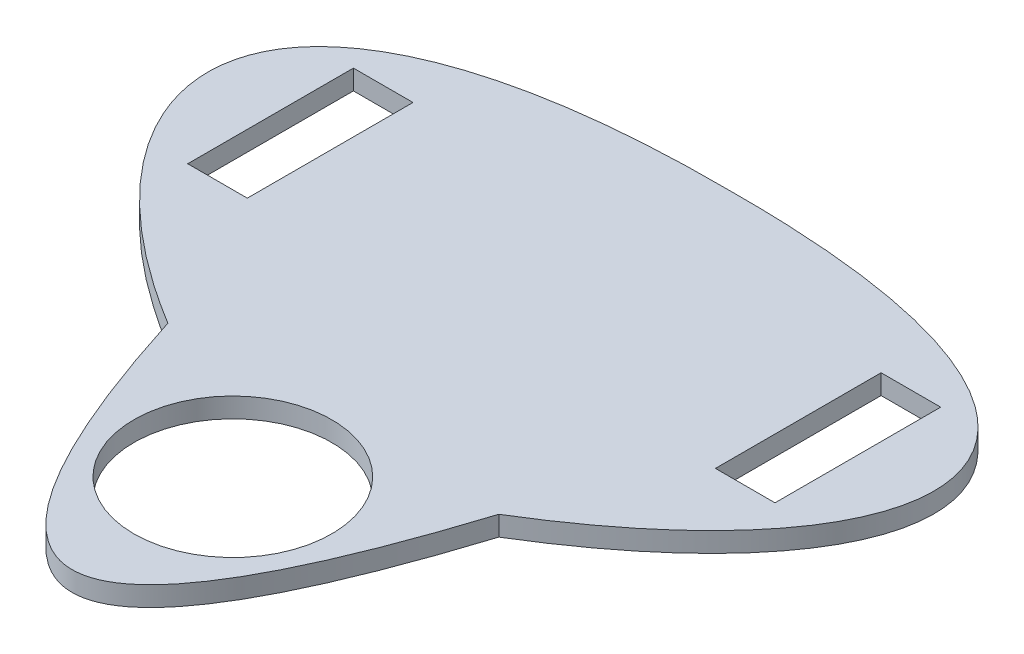
SolidWorks part; units mm, degrees
ref_plane "Front Plane" through (0, 0, 0) normal (0, 0, 1) x (1, 0, 0)
ref_plane "Top Plane" through (0, 0, 0) normal (0, 1, 0) x (1, 0, 0)
ref_plane "Right Plane" through (0, 0, 0) normal (1, 0, 0) x (0, 0, -1)
sketch "Sketch1" plane through (0, 0, 0) normal (0, 1, 0) x (1, 0, 0)
  line L0 (-25.8503, 0) -> (24.3232, 0) construction
  line L1 (24.3232, -39.6176) -> (-25.8503, -39.6176) construction
  line L2 (-25.8503, 0) -> (-25.8503, -39.6176) construction
  line L3 (24.3232, 0) -> (24.3232, -39.6176) construction
  line L4 (-0.7636, -39.6176) -> (-0.7636, 60) construction
  line L5 (-71.4362, 60) -> (64.5851, 60) construction
  line L6 (-40.7636, 54.1374) -> (-40.7636, 10.8247) construction
  line L7 (-55.7636, 35) -> (-0.7636, 35) construction
  line L8 (-40.7636, 42.7002) -> (-0.7636, 42.7002) construction
  line L9 (43.7533, 22.441) -> (34.7196, 22.441)
  line L10 (-45.2804, 47.559) -> (-36.2467, 47.559)
  line L11 (-45.2804, 47.559) -> (-45.2804, 22.441)
  line L12 (-45.2804, 22.441) -> (-36.2467, 22.441)
  line L13 (-36.2467, 47.559) -> (-36.2467, 22.441)
  line L14 (-45.2804, 47.559) -> (-36.2467, 22.441) construction
  line L15 (-45.2804, 22.441) -> (-36.2467, 47.559) construction
  line L16 (34.7196, 47.559) -> (34.7196, 22.441)
  line L17 (43.7533, 47.559) -> (34.7196, 47.559)
  line L18 (43.7533, 47.559) -> (43.7533, 22.441)
  line L19 (43.7533, 22.441) -> (34.7196, 47.559) construction
  line L20 (43.7533, 47.559) -> (34.7196, 22.441) construction
  line L21 (-25.8503, -15.2373) -> (24.3232, -15.2373) construction
  circle A0 centre (-0.7636, -15.2373) radius 15
  spline S0 degree 2 poles (-25.8503, 0) (-0.7636, -79.2352) (24.3232, 0) knots 0 0 0 1 1 1
  spline S1 degree 3 poles (-25.8503, 0) (-68.6705, 26.0498) (-69.9674, 60.482) (-0.7636, 60) knots 0 0 0 0 1 1 1 1
  spline S2 degree 3 poles (24.3232, 0) (67.1434, 26.0498) (68.4403, 60.482) (-0.7636, 60) knots 0 0 0 0 1 1 1 1
  point P18 (-40.7636, 35)
  point P27 (39.2364, 35)
extrude "Boss-Extrude1" add sketch "Sketch1" along normal blind 3
